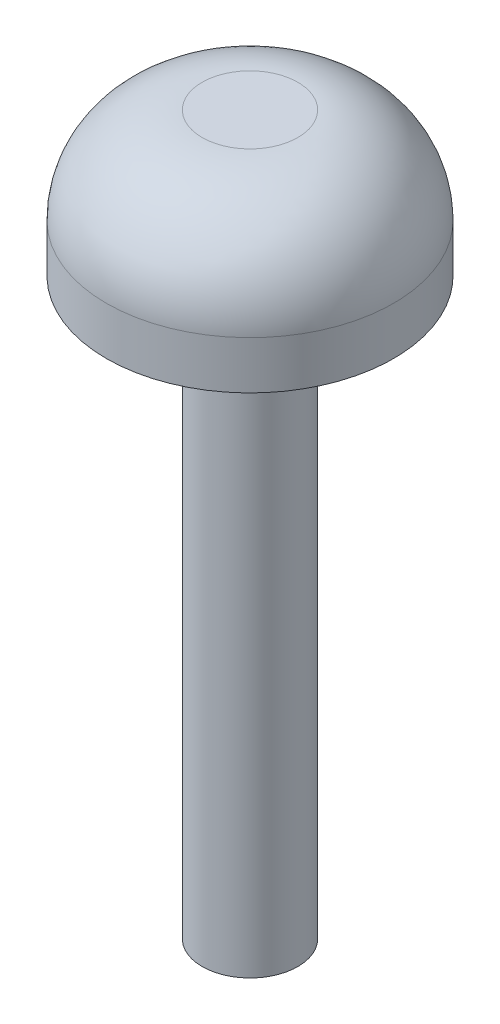
SolidWorks part; units mm, degrees
ref_plane "Front Plane" through (0, 0, 0) normal (0, 0, 1) x (1, 0, 0)
ref_plane "Top Plane" through (0, 0, 0) normal (0, 1, 0) x (1, 0, 0)
ref_plane "Right Plane" through (0, 0, 0) normal (1, 0, 0) x (0, 0, -1)
sketch "Sketch1" plane through (0, 0, 0) normal (0, 1, 0) x (1, 0, 0)
  circle A0 centre (0, 0) radius 0.5
  dimension "D1" = 1
extrude "Boss-Extrude1" add sketch "Sketch1" along normal blind 6
sketch "Sketch2" plane through (0, 6, 0) normal (0, 1, 0) x (1, 0, 0)
  circle A0 centre (0, 0) radius 1.5
  dimension "D1" = 3
extrude "Boss-Extrude2" add sketch "Sketch2" along normal blind 1.5
fillet "Fillet1" radius 1 1 edges at (0, 7.5, 1.5)
